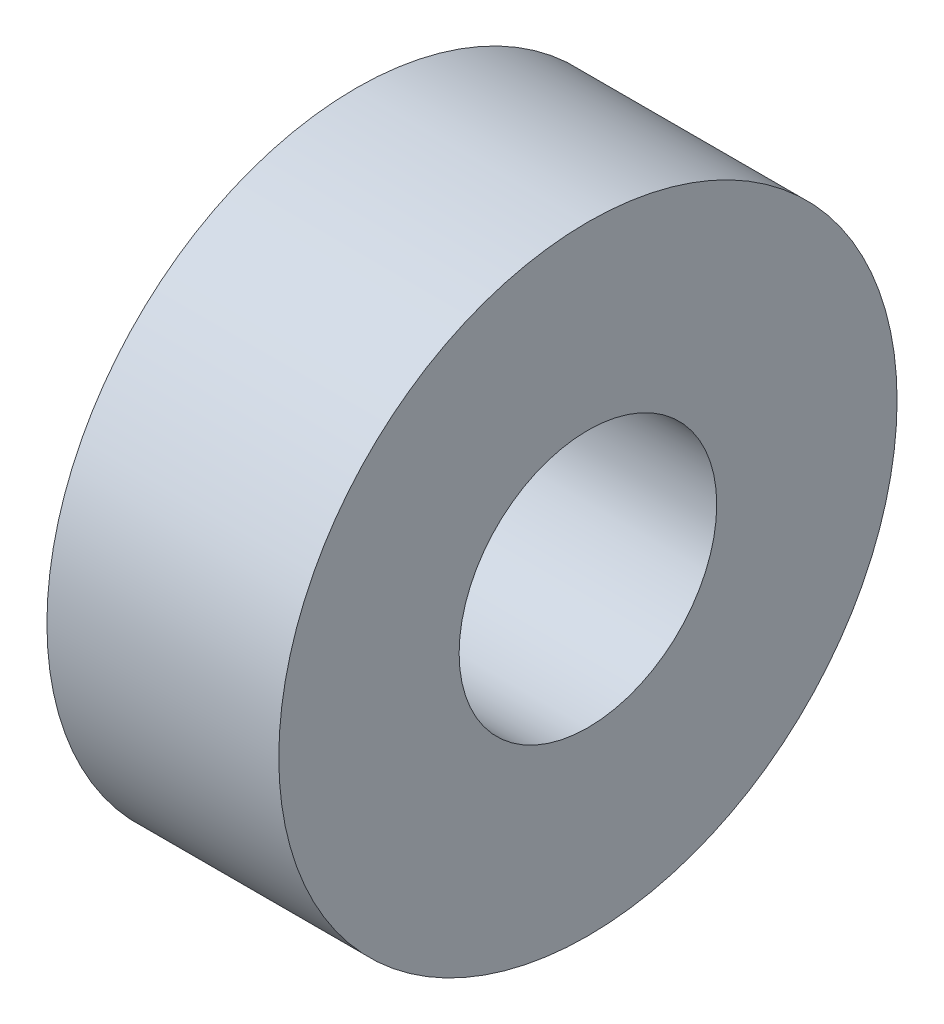
SolidWorks part; units mm, degrees
ref_plane "Front Plane" through (0, 0, 0) normal (0, 0, 1) x (1, 0, 0)
ref_plane "Top Plane" through (0, 0, 0) normal (0, 1, 0) x (1, 0, 0)
ref_plane "Right Plane" through (0, 0, 0) normal (1, 0, 0) x (0, 0, -1)
sketch "Sketch1" plane through (0, 0, 0) normal (0, 0, 1) x (1, 0, 0)
  line L0 (0, 5) -> (9, 5)
  line L1 (9, 5) -> (9, 12)
  line L2 (9, 12) -> (0, 12)
  line L3 (0, 12) -> (0, 5)
  line L4 (0, 0) -> (12.8798, 0) construction
  dimension "D1" = 12
  dimension "D2" = 5
  dimension "D3" = 9
revolve "Revolve1" add sketch "Sketch1" angle 360 about L4
